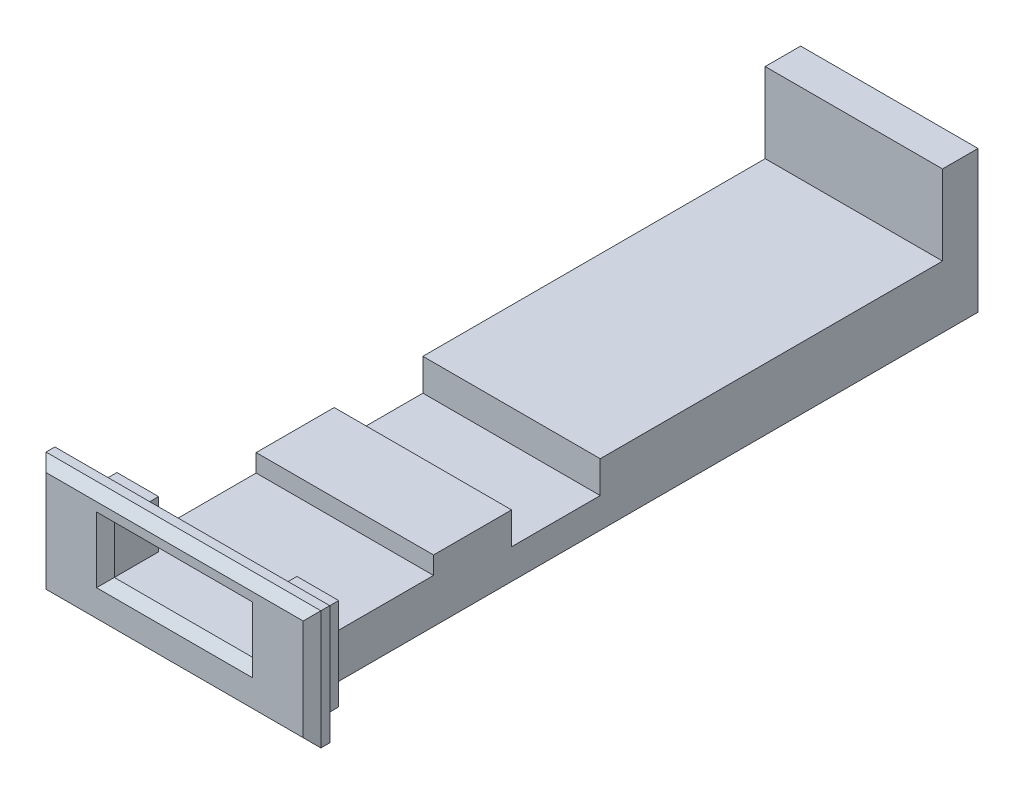
SolidWorks part; units mm, degrees
ref_plane "Front Plane" through (0, 0, 0) normal (0, 0, 1) x (1, 0, 0)
ref_plane "Top Plane" through (0, 0, 0) normal (0, 1, 0) x (1, 0, 0)
ref_plane "Right Plane" through (0, 0, 0) normal (1, 0, 0) x (0, 0, -1)
sketch "Sketch1" plane through (0, 0, 0) normal (1, 0, 0) x (0, 0, -1)
  line L0 (0, 0) -> (40.3, 0)
  line L1 (40.3, 0) -> (40.3, 8)
  line L2 (40.3, 8) -> (38.3, 8)
  line L3 (38.3, 8) -> (38.3, 3.5)
  line L4 (38.3, 3.5) -> (19, 3.5)
  line L5 (19, 3.5) -> (19, 1.7)
  line L6 (19, 1.7) -> (14, 1.7)
  line L7 (14, 1.7) -> (14, 3.5)
  line L8 (14, 3.5) -> (9.6, 3.5)
  line L9 (9.6, 3.5) -> (9.6, 2.5)
  line L10 (9.6, 2.5) -> (3, 2.5)
  line L13 (0, 6.7) -> (0, 0)
  line L14 (3, 2.5) -> (3, 5.2)
  line L15 (3, 5.2) -> (1, 5.2)
  line L16 (1, 5.2) -> (1, 6.7)
  line L17 (1, 6.7) -> (0, 6.7)
  dimension "D1" = 2
  dimension "D2" = 1
  dimension "D3" = 6.6
  dimension "D4" = 2
  dimension "D5" = 8
  dimension "D6" = 4.4
  dimension "D7" = 5
  dimension "D8" = 19.3
  dimension "D9" = 2.5
  dimension "D10" = 1
  dimension "D11" = 1.8
  dimension "D12" = 6.7
  dimension "D13" = 5.2
extrude "Boss-Extrude1" add sketch "Sketch1" along normal mid plane 15.5
sketch "Sketch2" plane through (0, 0, 0) normal (0, 1, 0) x (1, 0, 0)
  line L0 (-7.75, 0) -> (7.75, 0)
  line L1 (7.75, 0) -> (7.75, 1)
  line L2 (7.75, 1) -> (6.25, 1)
  line L3 (7.75, 1) -> (-7.75, 1) construction
  line L4 (6.25, 1) -> (6.25, 3)
  line L5 (7.75, 3) -> (-7.75, 3) construction
  line L6 (6.25, 3) -> (5, 3)
  line L7 (7.75, 3) -> (-7.75, 3) construction
  line L8 (5, 3) -> (5, 40.3)
  line L9 (5, 40.3) -> (-5, 40.3)
  line L10 (0, 40.3) -> (0, 0) construction
  line L11 (-5, 3) -> (-5, 40.3)
  line L12 (-6.25, 3) -> (-5, 3)
  line L13 (-6.25, 1) -> (-6.25, 3)
  line L14 (-7.75, 1) -> (-6.25, 1)
  line L15 (-7.75, 0) -> (-7.75, 1)
  line L16 (7.75, 40.3) -> (-7.75, 40.3) construction
  point P23 (5, 42.5712)
  dimension "D1" = 1.5
  dimension "D2" = 1.25
extrude "Cut-Extrude-Thin1" cut sketch "Sketch2" along normal through all thin
sketch "Sketch3" plane through (0, 0, 0) normal (0, 0, 1) x (1, 0, 0)
  line L0 (7.75, 0) -> (-7.75, 0) construction
  line L1 (-3.9, 2.5) -> (3.9, 2.5)
  line L2 (-3.9, 2.5) -> (-3.9, 5.2)
  line L3 (-3.9, 5.2) -> (3.9, 5.2)
  line L4 (3.9, 2.5) -> (3.9, 5.2)
  line L5 (7.75, 6.7) -> (7.75, 0) construction
  line L6 (-7.75, 6.7) -> (-7.75, 0) construction
  line L7 (7.75, 6.7) -> (-7.75, 6.7) construction
  dimension "2.5" = 2.5
  dimension "D2" = 3.85
  dimension "D3" = 3.85
  dimension "D4" = 1.5
extrude "Cut-Extrude1" cut sketch "Sketch3" against normal up to next
chamfer "Chamfer1" distance 0.5 angle 45 8 edges at (0, 6.7, 0) (7.75, 3.35, 0) (0, 0, 0) (-7.75, 3.35, 0) (3.9, 3.85, 0) (0, 5.2, 0) (-3.9, 3.85, 0) (0, 2.5, 0)
equation "\"D3@Sketch3\"=\"D2@Sketch3\""
